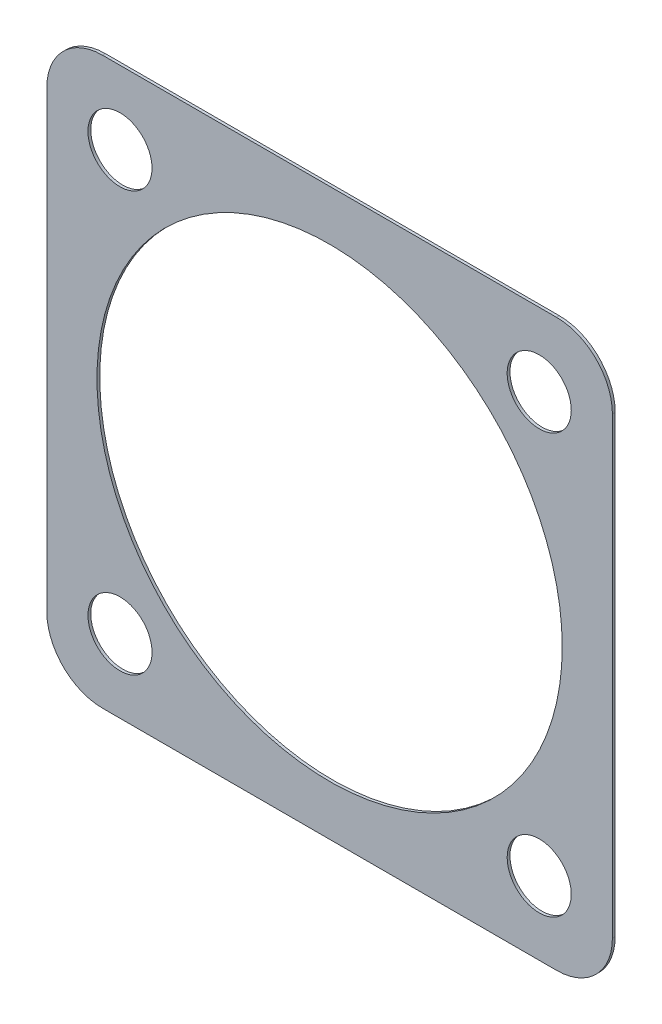
SolidWorks part; units mm, degrees
material "TESNIT BA-R"
ref_plane "Front Plane" through (0, 0, 0) normal (0, 0, 1) x (1, 0, 0)
ref_plane "Top Plane" through (0, 0, 0) normal (0, 1, 0) x (1, 0, 0)
ref_plane "Right Plane" through (0, 0, 0) normal (1, 0, 0) x (0, 0, -1)
sketch "Sketch1" plane through (0, 0, 0) normal (0, 0, 1) x (1, 0, 0)
  line L0 (0, 0) -> (0, 53.7378) construction
  line L1 (-40.75, 50.75) -> (40.75, 50.75)
  line L2 (-50.75, 40.75) -> (-50.75, -40.75)
  line L3 (-40.75, -50.75) -> (40.75, -50.75)
  line L4 (50.75, 40.75) -> (50.75, -40.75)
  line L5 (0, 0) -> (61.6092, 0) construction
  line L6 (0, 0) -> (37.6181, 37.6181) construction
  arc A0 (50.75, 40.75) -> (40.75, 50.75) centre (40.75, 40.75) ccw
  arc A1 (-50.75, 40.75) -> (-40.75, 50.75) centre (-40.75, 40.75) cw
  arc A2 (-50.75, -40.75) -> (-40.75, -50.75) centre (-40.75, -40.75) ccw
  arc A3 (50.75, -40.75) -> (40.75, -50.75) centre (40.75, -40.75) cw
  circle A4 centre (37.6181, 37.6181) radius 5.75
  circle A5 centre (-37.6181, 37.6181) radius 5.75
  circle A6 centre (-37.6181, -37.6181) radius 5.75
  circle A7 centre (37.6181, -37.6181) radius 5.75
  circle A8 centre (0, 0) radius 41.75
  circle A9 centre (0, 0) radius 53.2 construction
  point P10 (50.75, 50.75)
  point P17 (50.75, -50.75)
  dimension "D3" = 10
  dimension "D4" = 106.4
  dimension "D5" = 45
  dimension "D6" = 11.5
  dimension "D7" = 83.5
  dimension "D1" = 101.5
  dimension "D2" = 101.5
extrude "Extrude1" add sketch "Sketch1" along normal blind 0.5
